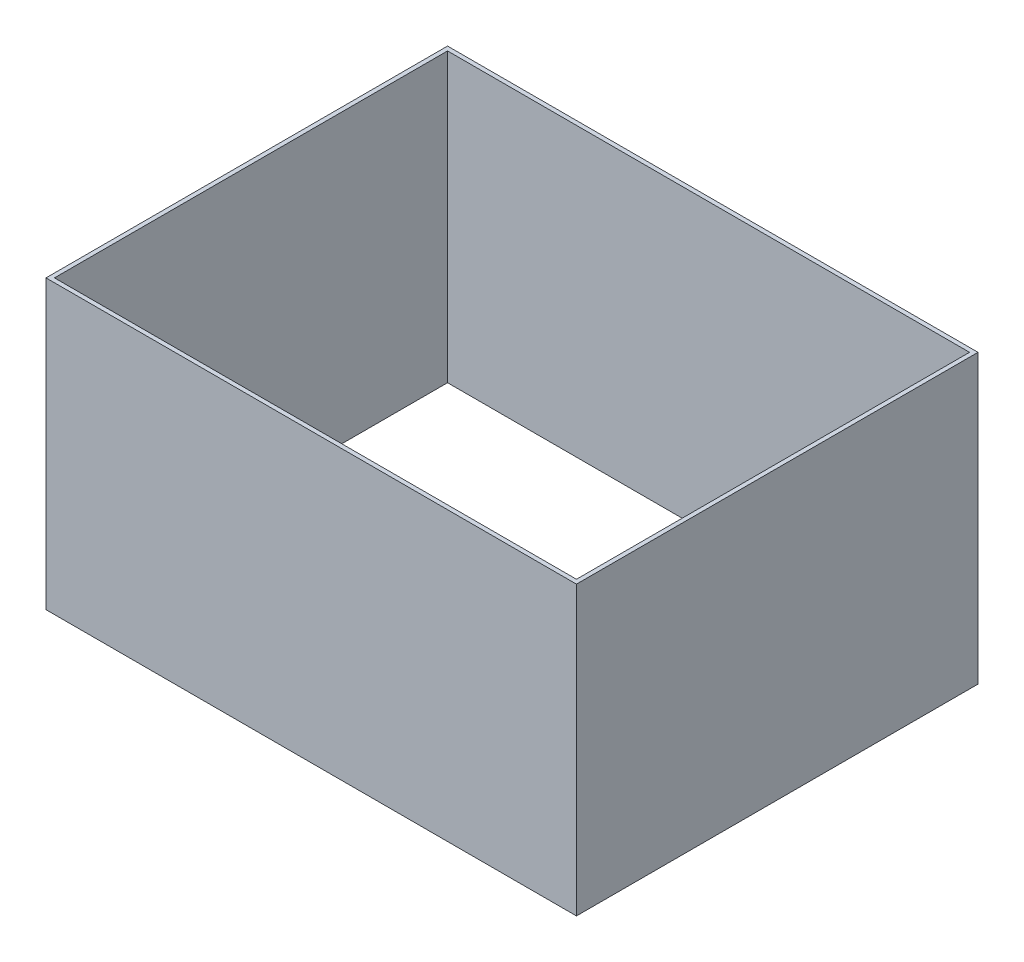
SolidWorks part; units mm, degrees
ref_plane "Спереди" through (0, 0, 0) normal (0, 0, 1) x (1, 0, 0)
ref_plane "Сверху" through (0, 0, 0) normal (0, 1, 0) x (1, 0, 0)
ref_plane "Справа" through (0, 0, 0) normal (1, 0, 0) x (0, 0, -1)
ref_plane "Плоскость4"
sketch "Эскиз1" plane through (0, 0, 0) normal (0, 1, 0) x (-1, 0, 0)
  line L0 (-1645.387, -1010.0309) -> (864.613, -1010.0309)
  line L1 (864.613, -1010.0309) -> (864.613, 889.9691)
  line L2 (864.613, 889.9691) -> (-1645.387, 889.9691)
  line L3 (-1645.387, 889.9691) -> (-1645.387, -1010.0309)
  line L4 (-1625.387, 869.9691) -> (844.613, 869.9691)
  line L5 (844.613, 869.9691) -> (844.613, -990.0309)
  line L6 (844.613, -990.0309) -> (-1625.387, -990.0309)
  line L7 (-1625.387, -990.0309) -> (-1625.387, 869.9691)
  dimension "D1" = 2470
  dimension "D2" = 1860
extrude "Выдавливание1" add sketch "Эскиз1" along normal blind 1359.75 contours L2 L3 L0 L1 L6 L7 L4 L5
